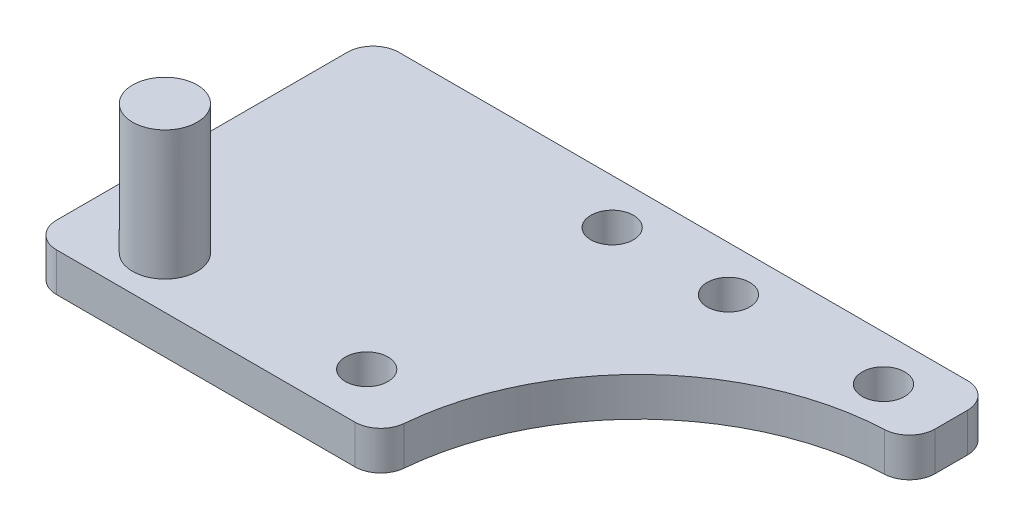
SolidWorks part; units mm, degrees
material "ABS"
ref_plane "Front Plane" through (0, 0, 0) normal (0, 0, 1) x (1, 0, 0)
ref_plane "Top Plane" through (0, 0, 0) normal (0, 1, 0) x (1, 0, 0)
ref_plane "Right Plane" through (0, 0, 0) normal (1, 0, 0) x (0, 0, -1)
sketch "Sketch1" plane through (0, 0, 0) normal (0, 1, 0) x (1, 0, 0)
  line L5 (31, 0) -> (29.35, 0) construction
  line L6 (9, -4) -> (9, 22.4937)
  line L10 (29.35, 0) -> (76.1971, 0) construction
  line L13 (57, 21) -> (57, 16)
  line L14 (9, -4) -> (36, -4)
  line L16 (21, 22.4937) -> (57, 22.4937)
  line L17 (57, 22.4937) -> (57, 21)
  line L19 (9, 22.4937) -> (21, 22.4937)
  circle A4 centre (31, 19) radius 1.65
  circle A5 centre (40, 19) radius 1.65
  circle A6 centre (52, 19) radius 1.65
  circle A7 centre (31, 0) radius 1.65
  arc A14 (36, -4) -> (57, 16) centre (56, -3.975) cw
  point P0 (0, 0)
  dimension "D4" = 9
  dimension "D5" = 12
  dimension "D6" = 56
  dimension "D14" = 3.3
  dimension "D11" = 5
  dimension "D13" = 3.3
  dimension "D29" = 4
  dimension "D30" = 20
  dimension "D9" = 3.3
  dimension "D10" = 3.3
  dimension "D7" = 57
  dimension "D8" = 22.4937
  dimension "D15" = 19
  dimension "D22" = 9
  dimension "D23" = 21
  dimension "D27" = 5
  dimension "25" = 27
extrude "Main Body" add sketch "Sketch1" along normal blind 3
sketch "Sketch2" plane through (0, 3, 0) normal (0, 1, 0) x (1, 0, 0)
  line L0 (9, 22.4937) -> (9, -4) construction
  line L1 (9, -4) -> (36, -4) construction
  circle A0 centre (15.3807, 0) radius 2.5
  dimension "D1" = 5
  dimension "D2" = 6.3807
  dimension "D3" = 4
extrude "Connecting Rod" add sketch "Sketch2" along normal blind 10
fillet "Fillet1" radius 2 5 edges at (57, 1.5, -22.4937) (57, 1.5, -16) (36, 1.5, 4) (9, 1.5, 4) (9, 1.5, -22.4937)
